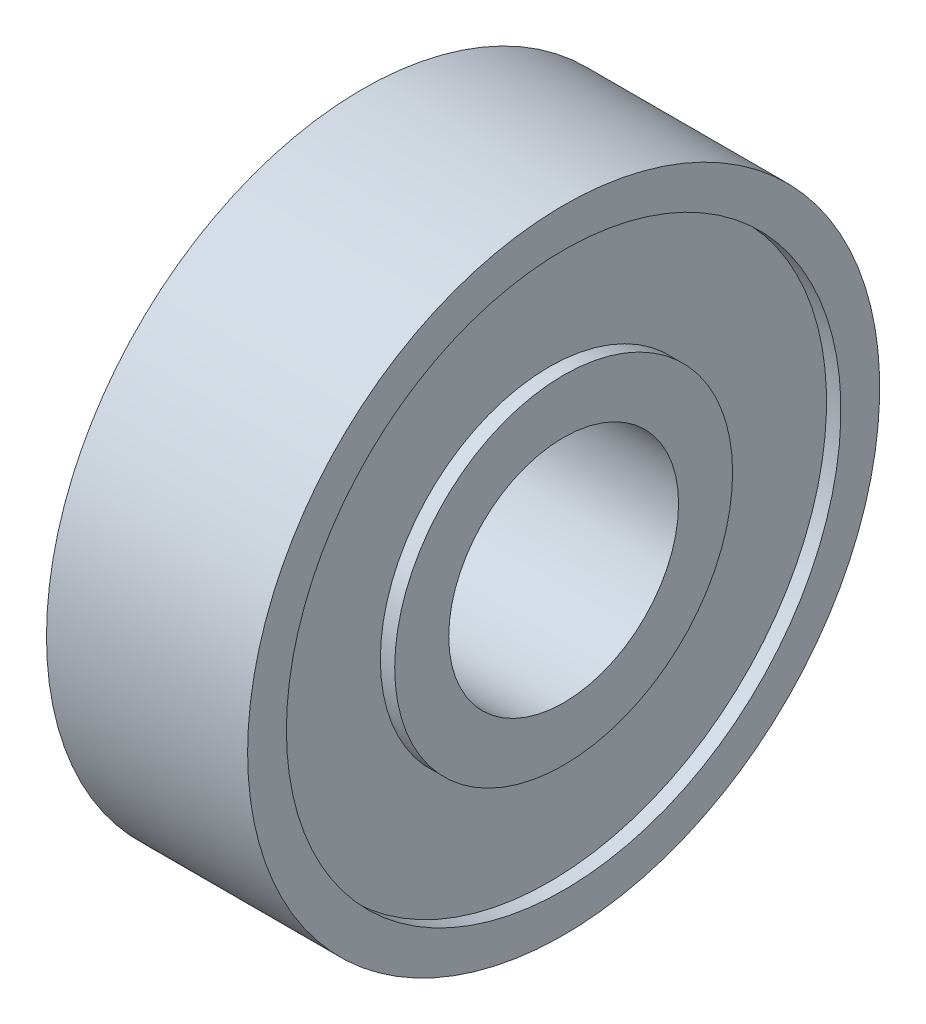
SolidWorks part; units mm, degrees
ref_plane "Front Plane" through (0, 0, 0) normal (0, 0, 1) x (1, 0, 0)
ref_plane "Top Plane" through (0, 0, 0) normal (0, 1, 0) x (1, 0, 0)
ref_plane "Right Plane" through (0, 0, 0) normal (1, 0, 0) x (0, 0, -1)
sketch "Sketch2" plane through (0, 0, 0) normal (0, 1, 0) x (1, 0, 0)
  line L0 (0, 0) -> (0, 18.219) construction
  line L1 (0, 0) -> (28.0939, 0) construction
  line L2 (3, 9.65) -> (3.5, 9.65)
  line L3 (-3.5, 11) -> (3.5, 11)
  line L4 (-3.5, 9.65) -> (-3.5, 5.88) construction
  line L5 (3, 5.88) -> (3.5, 5.88)
  line L6 (3.5, 11) -> (3.5, 9.65)
  line L7 (-3, 9.65) -> (3, 9.65) construction
  line L8 (-3.5, 5.88) -> (-3.5, 4)
  line L9 (-3, 5.88) -> (3, 5.88) construction
  line L10 (3, 9.65) -> (3, 5.88)
  line L11 (3.5, 9.65) -> (3.5, 5.88) construction
  line L12 (-3, 9.65) -> (-3, 5.88)
  line L13 (-3.5, 4) -> (3.5, 4)
  line L14 (3.5, 5.88) -> (3.5, 4)
  line L15 (-3.5, 11) -> (-3.5, 9.65)
  line L16 (-3, 5.88) -> (-3.5, 5.88)
  line L17 (-3, 9.65) -> (-3.5, 9.65)
  point P17 (0, 5.88)
  point P18 (0, 9.65)
  point P19 (0, 4)
  point P20 (0, 11)
  dimension "D1" = 4
  dimension "D2" = 3.5
  dimension "D3" = 0.5
  dimension "D4" = 1.35
  dimension "D5" = 1.88
  dimension "D6" = 11
revolve "Revolve2" add sketch "Sketch2" angle 360 about L1
